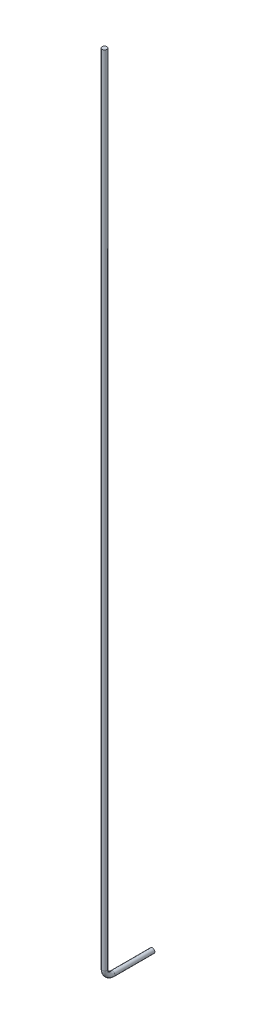
SolidWorks part; units mm, degrees
ref_plane "正面" through (0, 0, 0) normal (0, 0, 1) x (1, 0, 0)
ref_plane "平面" through (0, 0, 0) normal (0, 1, 0) x (1, 0, 0)
ref_plane "右側面" through (0, 0, 0) normal (1, 0, 0) x (0, 0, -1)
sketch "ｽｹｯﾁ1" plane through (0, 0, 0) normal (0, 0, 1) x (1, 0, 0)
  circle A0 centre (0, 0) radius 1.5
  dimension "D1" = 3
extrude "ﾎﾞｽ - 押し出し1" add sketch "ｽｹｯﾁ1" along normal blind 20
sketch "ｽｹｯﾁ2" plane through (0, 0, 20) normal (0, 0, 1) x (1, 0, 0)
  circle A1 centre (0, 0) radius 1.5
  circle A2 centre (0, 0) radius 1.5
  dimension "D1" = 0
sketch "ｽｹｯﾁ3" plane through (0, 0, 0) normal (1, 0, 0) x (0, 0, -1)
  line L0 (-20, 0) -> (-25, 0)
  line L1 (-20, 1.5) -> (-20, -1.5) construction
  line L2 (-30, 5) -> (-30, 505)
  line L3 (-20, 1.5) -> (-20, -1.5) construction
  arc A0 (-25, 0) -> (-30, 5) centre (-25, 5) cw
  point P8 (-30, 0)
  dimension "D2" = 5
  dimension "D1" = 10
  dimension "D3" = 500
sweep "ｽｲｰﾌﾟ1" add profiles "ｽｹｯﾁ2" path "ｽｹｯﾁ3"
